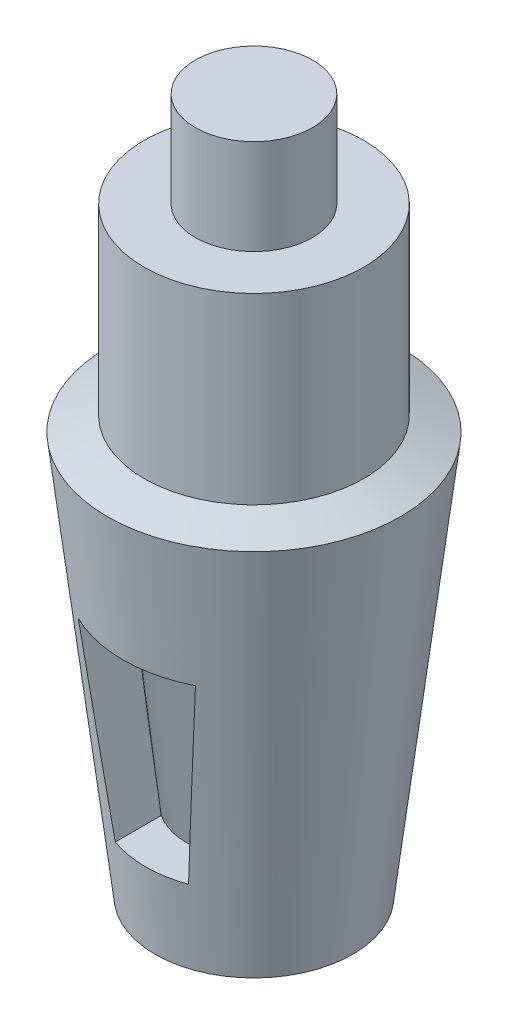
SolidWorks part; units mm, degrees
ref_plane "Front Plane" through (0, 0, 0) normal (0, 0, 1) x (1, 0, 0)
ref_plane "Top Plane" through (0, 0, 0) normal (0, 1, 0) x (1, 0, 0)
ref_plane "Right Plane" through (0, 0, 0) normal (1, 0, 0) x (0, 0, -1)
sketch "Sketch1" plane through (0, 0, 0) normal (0, 0, 1) x (1, 0, 0)
  line L0 (-233.3686, 0) -> (329.7236, 0) construction
  line L1 (0, 273.925) -> (0, -218.5501) construction
  line L2 (16, 0) -> (27, 0)
  line L3 (27, 0) -> (40, 110)
  line L4 (40, 110) -> (30, 114)
  line L5 (30, 114) -> (30, 164)
  line L6 (30, 164) -> (16, 164)
  line L7 (16, 164) -> (16, 190)
  line L8 (16, 190) -> (0, 190)
  line L9 (0, 190) -> (0, 147.5189)
  line L10 (0, 147.5189) -> (20, 147.5189)
  line L11 (20, 147.5189) -> (20, 91.5189)
  line L12 (24.973, 86) -> (16, 0)
  line L13 (0, 84) -> (16, 84)
  line L14 (16, 84) -> (10, 22)
  line L15 (10, 22) -> (0, 22)
  line L16 (24.973, 86) -> (0, 86)
  arc A0 (20, 91.5189) -> (24.973, 86) centre (20, 86.5189) cw
  dimension "D12" = 5
  dimension "D1" = 16
  dimension "D2" = 20
  dimension "D3" = 50
  dimension "D4" = 16
  dimension "D5" = 27
  dimension "D6" = 26
  dimension "D7" = 30
  dimension "D8" = 16
  dimension "D9" = 110
  dimension "D10" = 4
  dimension "D11" = 40
  dimension "D13" = 10
  dimension "D14" = 22
  dimension "D15" = 62
  dimension "D16" = 2
  dimension "D17" = 5.5189
  dimension "D18" = 56
revolve "Revolve1" add sketch "Sketch1" angle 360 about L1
sketch "Sketch2" plane through (0, 0, 0) normal (0, 0, 1) x (1, 0, 0)
  line L0 (0, -11.2559) -> (0, 195.1538) construction
  line L1 (-10, 22) -> (10, 22)
  line L2 (10, 22) -> (16, 74)
  line L3 (16, 74) -> (-16, 74)
  line L4 (-16, 74) -> (-10, 22)
  line L5 (24.973, 86) -> (0, 86) construction
  dimension "D1" = 20
  dimension "D2" = 22
  dimension "D3" = 32
  dimension "D4" = 16
  dimension "D5" = 12
extrude "Cut-Extrude1" cut sketch "Sketch2" against normal through all both and the other way through all
